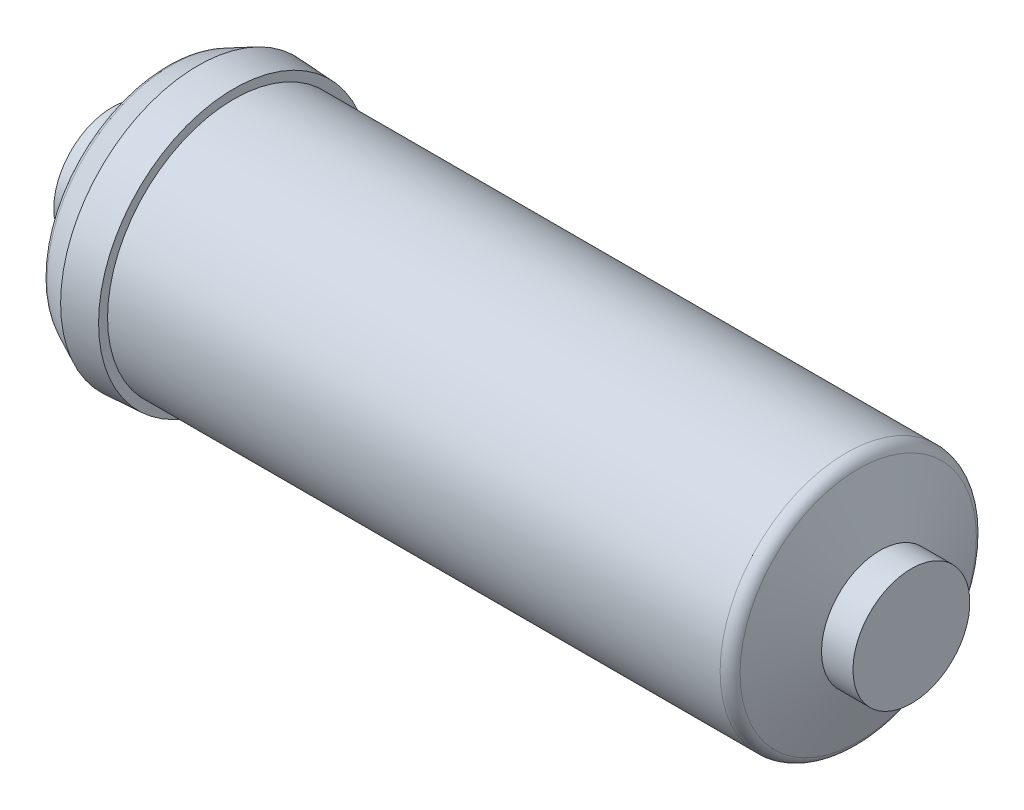
SolidWorks part; units mm, degrees
ref_plane "Front Plane" through (0, 0, 0) normal (0, 0, 1) x (1, 0, 0)
ref_plane "Top Plane" through (0, 0, 0) normal (0, 1, 0) x (1, 0, 0)
ref_plane "Right Plane" through (0, 0, 0) normal (1, 0, 0) x (0, 0, -1)
sketch "Sketch1" plane through (0, 0, 0) normal (0, 0, 1) x (1, 0, 0)
  line L0 (0, 0) -> (203.2, 0) construction
  line L1 (0, 0) -> (0, 14.859)
  line L2 (0, 14.859) -> (8.001, 14.859)
  line L3 (8.001, 14.859) -> (13.9177, 31.115)
  line L4 (13.9177, 31.115) -> (21.7917, 34.925)
  line L5 (21.7917, 34.925) -> (30.9357, 34.417)
  line L6 (30.9357, 34.417) -> (30.9357, 32.131)
  line L7 (30.9357, 32.131) -> (188.9125, 32.131)
  line L8 (188.9125, 32.131) -> (195.199, 14.859)
  line L9 (195.199, 14.859) -> (203.2, 14.859)
  line L10 (203.2, 14.859) -> (203.2, 0)
  line L11 (0, 0) -> (203.2, 0)
  point P3 (30.5124, 33.2838)
  point P13 (1.5761, 14.859)
  point P14 (28.6522, 34.417)
  point P15 (23.1793, 34.417)
  dimension "D1" = 64.262
  dimension "D2" = 69.85
  dimension "D3" = 2.286
  dimension "D4" = 29.718
  dimension "D5" = 8.001
  dimension "D6" = 110
  dimension "D7" = 62.23
  dimension "D8" = 110
  dimension "D9" = 203.2
  dimension "D10" = 17.018
  dimension "D11" = 9.144
revolve "Revolve1" add sketch "Sketch1" angle 360 about L0
fillet "Fillet1" radius 3.175 2 edges at (188.9125, 0, 32.131) (13.9177, 0, 31.115)
